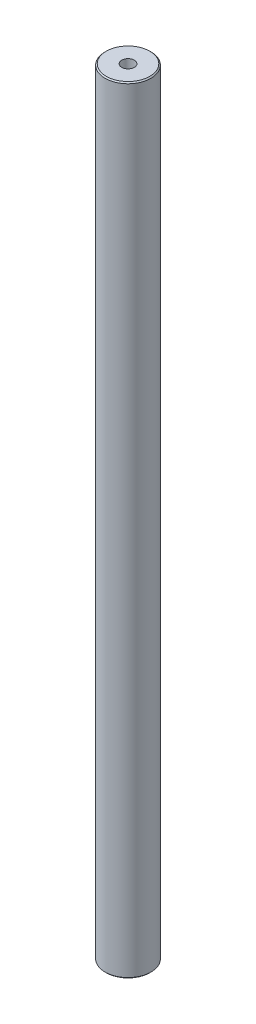
SolidWorks part; units mm, degrees
ref_plane "Plano frontal" through (0, 0, 0) normal (0, 0, 1) x (1, 0, 0)
ref_plane "Plano superior" through (0, 0, 0) normal (0, 1, 0) x (1, 0, 0)
ref_plane "Plano direito" through (0, 0, 0) normal (1, 0, 0) x (0, 0, -1)
sketch "Esboço1" plane through (0, 0, 0) normal (0, 0, 1) x (1, 0, 0)
  line L0 (1.65, 205.2) -> (0, 205.2)
  line L1 (0, 205.2) -> (0, 22)
  line L2 (0, 22) -> (1.65, 22)
  line L3 (1.65, 22) -> (1.65, 12)
  line L4 (1.65, 12) -> (5.7, 12)
  line L5 (5.7, 12) -> (6, 12.3)
  line L6 (6, 12.3) -> (6, 214.9)
  line L7 (6, 214.9) -> (5.7, 215.2)
  line L8 (5.7, 215.2) -> (1.65, 215.2)
  line L9 (1.65, 215.2) -> (1.65, 205.2)
  line L10 (0, 215.2) -> (0, 12) construction
revolve "Revolução1" add sketch "Esboço1" angle 360 about L10
